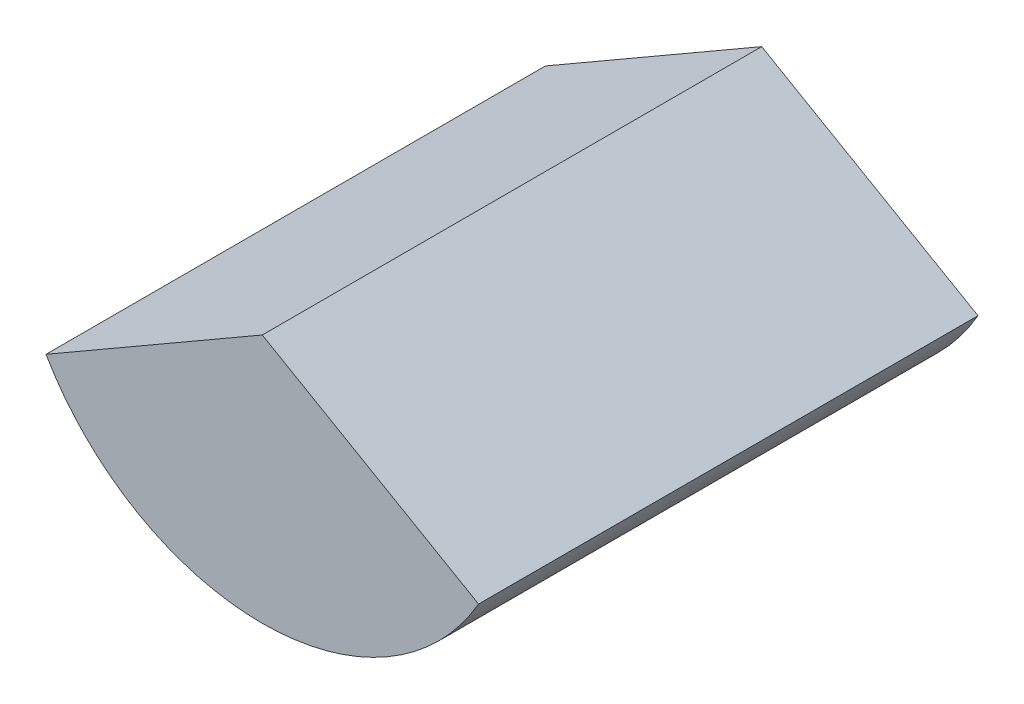
SolidWorks part; units mm, degrees
ref_plane "Alzado" through (0, 0, 0) normal (0, 0, 1) x (1, 0, 0)
ref_plane "Planta" through (0, 0, 0) normal (0, 1, 0) x (1, 0, 0)
ref_plane "Vista lateral" through (0, 0, 0) normal (1, 0, 0) x (0, 0, -1)
sketch "Croquis1" plane through (0, 0, 0) normal (0, 0, 1) x (1, 0, 0)
  line L1 (0, 0) -> (-21.6506, -12.5)
  line L2 (0, 0) -> (21.6506, -12.5)
  arc A0 (-21.6506, -12.5) -> (21.6506, -12.5) centre (0, 0) ccw
  dimension "D1" = 50
  dimension "D2" = 120
extrude "Saliente-Extruir1" add sketch "Croquis1" along normal blind 50
sketch "Croquis2" plane through (0, 0, 0) normal (0, 0, -1) x (-1, 0, 0)
  circle A0 centre (0, -13.6117) radius 5
  dimension "D1" = 10
extrude "Cortar-Extruir1" cut sketch "Croquis2" against normal blind 10
